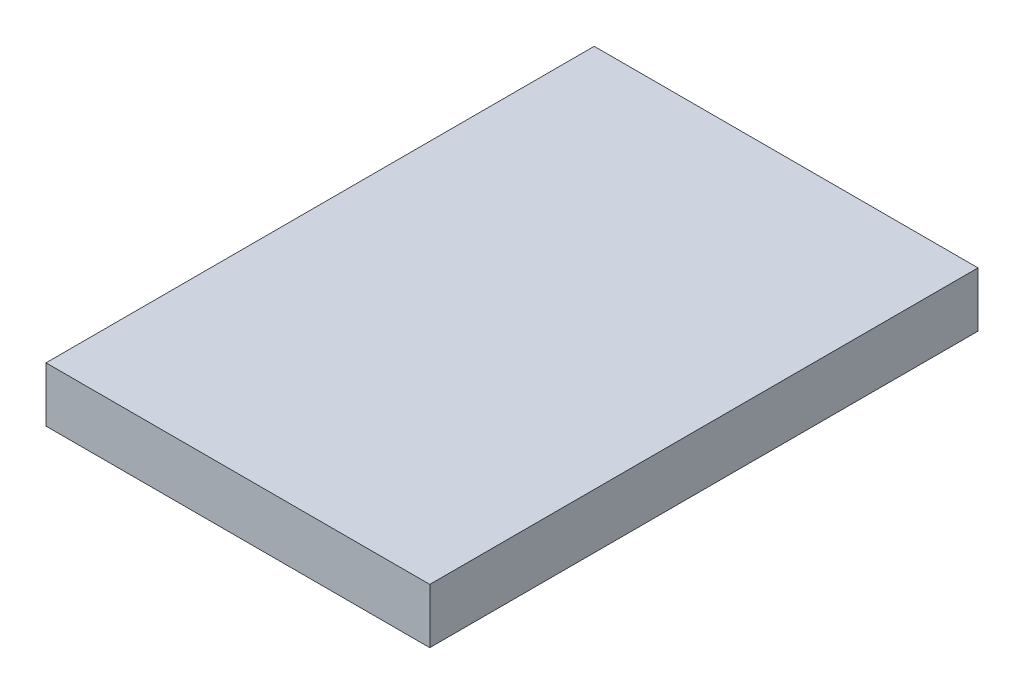
SolidWorks part; units mm, degrees
material "PE High Density"
ref_plane "Front Plane" through (0, 0, 0) normal (0, 0, 1) x (1, 0, 0)
ref_plane "Top Plane" through (0, 0, 0) normal (0, 1, 0) x (1, 0, 0)
ref_plane "Right Plane" through (0, 0, 0) normal (1, 0, 0) x (0, 0, -1)
sketch "Sketch1" plane through (0, 0, 0) normal (0, 1, 0) x (1, 0, 0)
  line L1 (0, 0) -> (88.9, 0)
  line L2 (0, 0) -> (0, 127)
  line L3 (0, 127) -> (88.9, 127)
  line L4 (88.9, 0) -> (88.9, 127)
  dimension "D1" = 88.9
  dimension "D2" = 127
extrude "Boss-Extrude1" add sketch "Sketch1" along normal blind 12.7
hole_wizard "CSK for 1/4 Flat Head Machine Screw1" [suppressed] positions "Sketch2" profile "Sketch3" countersink size "1/4" standard "ANSI Inch"
sketch "Sketch2" plane through (0, 12.7, 0) normal (0, 1, 0) x (-1, 0, 0)
  line L0 (-44.45, -127) -> (-44.45, -111.125) construction
  line L1 (-88.9, -127) -> (0, -127) construction
  line L3 (-44.45, 0) -> (-44.45, -15.875) construction
  line L4 (0, 0) -> (-88.9, 0) construction
  point P2 (-44.45, -111.125)
  point P8 (-44.45, -15.875)
  dimension "D1" = 15.875
sketch "Sketch3" plane through (44.45, 12.7, -15.875) normal (1, 0, 0) x (0, 0, 1)
  line L0 (0, 0) -> (0, 12.7)
  line L1 (0, 12.7) -> (3.3782, 12.7)
  line L2 (3.3782, 12.7) -> (3.3782, 5.0449)
  line L3 (3.3782, 5.0449) -> (7.7637, 0)
  line L5 (7.7637, 0) -> (0, 0)
  line L6 (-3.3782, 5.0449) -> (-7.7637, 0) construction
  line L11 (0, -6.35) -> (0, 107.95) construction
  dimension "Thru Hole Dia." = 6.7564
  dimension "Thru Hole Depth" = 12.7
  dimension "Near C'Sink Dia." = 15.5274
  dimension "Near C'Sink Angle" = 82
fillet "Fillet1" [suppressed] radius 6.35
fillet "Fillet2" [suppressed] radius 6.35
